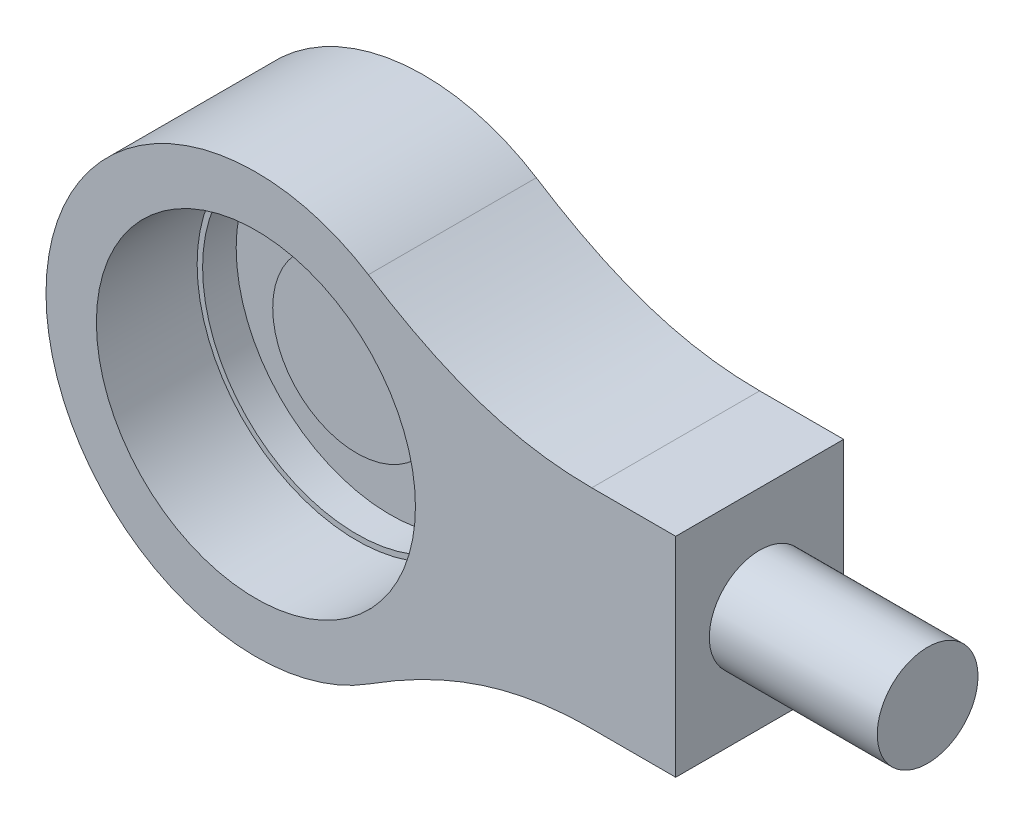
SolidWorks part; units mm, degrees
ref_plane "Front Plane" through (0, 0, 0) normal (0, 0, 1) x (1, 0, 0)
ref_plane "Top Plane" through (0, 0, 0) normal (0, 1, 0) x (1, 0, 0)
ref_plane "Right Plane" through (0, 0, 0) normal (1, 0, 0) x (0, 0, -1)
sketch "Sketch1" plane through (0, 0, 0) normal (0, 0, 1) x (1, 0, 0)
  line L0 (-18.4429, 0) -> (30.3885, 0) construction
  line L2 (20, 6.2152) -> (25, 6.2152)
  line L4 (20, -6.2152) -> (25, -6.2152)
  line L5 (25, 6.2152) -> (25, -6.2152)
  line L6 (15, 6.2152) -> (25, -6.2152) construction
  line L7 (15, -6.2152) -> (25, 6.2152) construction
  arc A0 (6.6976, 10.5542) -> (6.6976, -10.5542) centre (0, 0) ccw
  circle A1 centre (0, 0) radius 9.5
  spline S0 degree 3 poles (20, 6.2152) (14.928, 6.2152) (10.8915, 7.8929) (6.6976, 10.5542) knots 0 0 0 0 1 1 1 1
  spline S1 degree 3 poles (20, -6.2152) (14.928, -6.2152) (10.8915, -7.8929) (6.6976, -10.5542) knots 0 0 0 0 1 1 1 1
  point P6 (20, 0)
  dimension "D1" = 19
  dimension "D2" = 25
  dimension "D3" = 10
  dimension "D4" = 20
extrude "Boss-Extrude1" add sketch "Sketch1" along normal blind 10
sketch "Sketch2" plane through (0, 0, 0) normal (0, 0, -1) x (-1, 0, 0)
  circle A0 centre (0, 0) radius 12.5
extrude "Boss-Extrude2" add sketch "Sketch2" against normal blind 2
sketch "Sketch3" plane through (0, 0, 0) normal (0, 0, -1) x (-1, 0, 0)
  circle A0 centre (0, 0) radius 5
  dimension "D1" = 10
extrude "Boss-Extrude3" add sketch "Sketch3" against normal blind 4
sketch "Sketch4" plane through (0, 0, 0) normal (0, 0, -1) x (-1, 0, 0)
  circle A0 centre (0, 0) radius 9.175
  circle A1 centre (0, 0) radius 12.5
  dimension "D1" = 18.35
extrude "Boss-Extrude5" add sketch "Sketch4" against normal blind 4
sketch "Sketch5" plane through (25, 0, 0) normal (1, 0, 0) x (0, 0, -1)
  circle A0 centre (-5, 0) radius 3
  dimension "D1" = 6
extrude "Boss-Extrude6" add sketch "Sketch5" along normal blind 10
